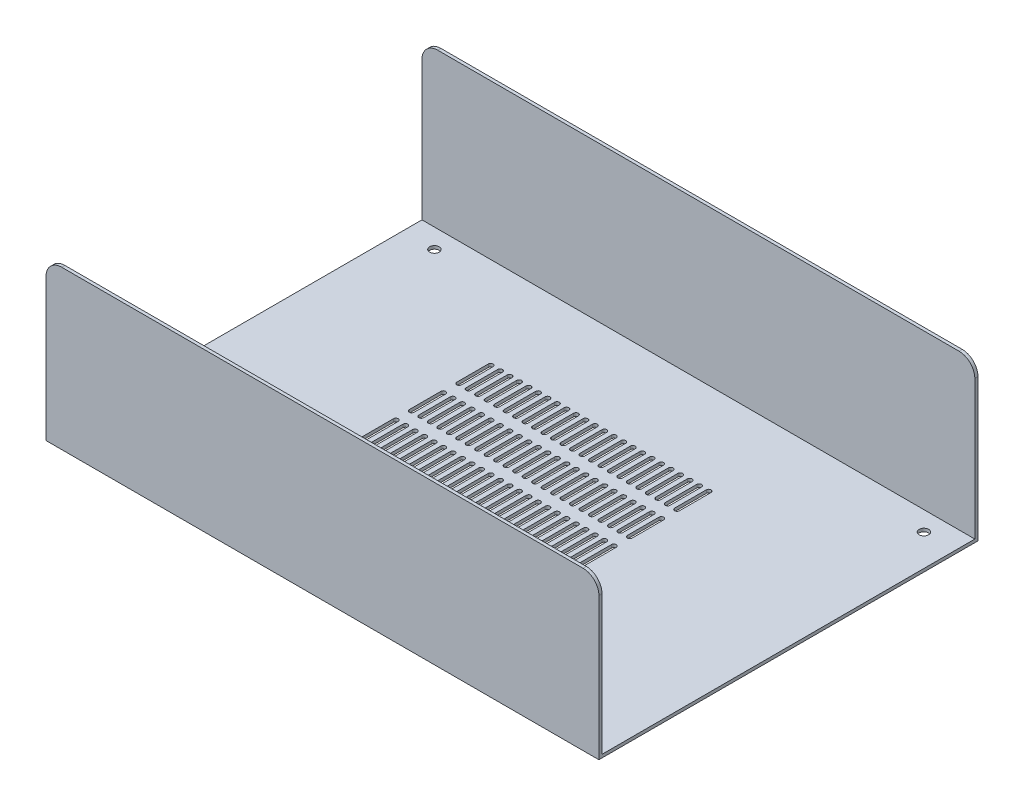
SolidWorks part; units mm, degrees
ref_plane "Front Plane" through (0, 0, 0) normal (0, 0, 1) x (1, 0, 0)
ref_plane "Top Plane" through (0, 0, 0) normal (0, 1, 0) x (1, 0, 0)
ref_plane "Right Plane" through (0, 0, 0) normal (1, 0, 0) x (0, 0, -1)
sketch "Sketch1" plane through (0, 0, 0) normal (0, 1, 0) x (1, 0, 0)
  line L1 (-87.5, 60) -> (87.5, 60)
  line L2 (-87.5, 60) -> (-87.5, -60)
  line L3 (-87.5, -60) -> (87.5, -60)
  line L4 (87.5, 60) -> (87.5, -60)
  point P4 (0, -60)
  point P6 (87.5, 0)
  dimension "D1" = 175
  dimension "D2" = 120
extrude "Extrude1" add sketch "Sketch1" along normal blind 1
sketch "Sketch2" plane through (0, 0, 60) normal (0, 0, 1) x (1, 0, 0)
  line L0 (-87.5, 1) -> (87.5, 1) construction
  line L1 (-82.5, 50) -> (82.5, 50)
  line L2 (-87.5, 45) -> (-87.5, 1)
  line L3 (-87.5, 1) -> (87.5, 1)
  line L4 (87.5, 45) -> (87.5, 1)
  arc A0 (-82.5, 50) -> (-87.5, 45) centre (-82.5, 45) ccw
  arc A1 (82.5, 50) -> (87.5, 45) centre (82.5, 45) cw
  point P9 (-87.5, 50)
  dimension "D2" = 5
  dimension "D1" = 49
extrude "Extrude2" add sketch "Sketch2" against normal blind 1
mirror "Mirror1" about plane through (0, 0, 0) normal (0, 0, 1) of "Extrude2"
sketch "Sketch3" plane through (0, 0, 0) normal (0, -1, 0) x (1, 0, 0)
  circle A0 centre (-77.42, 51.92) radius 1.5
  circle A2 centre (77.52, 51.92) radius 1.5
  circle A3 centre (77.52, 51.92) radius 1.5 construction
  circle A4 centre (77.52, -52.86) radius 1.5
  circle A6 centre (-77.42, -52.86) radius 1.5
  circle A8 centre (-77.42, -52.86) radius 1.5 construction
  circle A9 centre (77.52, -52.86) radius 1.5 construction
extrude "Cut-Extrude1" cut sketch "Sketch3" against normal through all
sketch "Sketch4" plane through (0, 0, 0) normal (0, -1, 0) x (1, 0, 0)
  line L0 (-37.5, 10) -> (-37.5, 0)
  line L1 (-36, 10) -> (-36, 0)
  line L2 (-87.5, -60) -> (-87.5, 60) construction
  line L146 (-87.5, 60) -> (87.5, 60) construction
  line L147 (-34.5, 10) -> (-34.5, 0)
  line L148 (-33, 10) -> (-33, 0)
  line L149 (-31.5, 10) -> (-31.5, 0)
  line L150 (-30, 10) -> (-30, 0)
  line L151 (-28.5, 10) -> (-28.5, 0)
  line L152 (-27, 10) -> (-27, 0)
  line L153 (-25.5, 10) -> (-25.5, 0)
  line L154 (-24, 10) -> (-24, 0)
  line L155 (-22.5, 10) -> (-22.5, 0)
  line L156 (-21, 10) -> (-21, 0)
  line L157 (-19.5, 10) -> (-19.5, 0)
  line L158 (-18, 10) -> (-18, 0)
  line L159 (-16.5, 10) -> (-16.5, 0)
  line L160 (-15, 10) -> (-15, 0)
  line L161 (-13.5, 10) -> (-13.5, 0)
  line L162 (-12, 10) -> (-12, 0)
  line L163 (-10.5, 10) -> (-10.5, 0)
  line L164 (-9, 10) -> (-9, 0)
  line L165 (-7.5, 10) -> (-7.5, 0)
  line L166 (-6, 10) -> (-6, 0)
  line L167 (-4.5, 10) -> (-4.5, 0)
  line L168 (-3, 10) -> (-3, 0)
  line L169 (-1.5, 10) -> (-1.5, 0)
  line L170 (0, 10) -> (0, 0)
  line L171 (1.5, 10) -> (1.5, 0)
  line L172 (3, 10) -> (3, 0)
  line L173 (4.5, 10) -> (4.5, 0)
  line L174 (6, 10) -> (6, 0)
  line L175 (7.5, 10) -> (7.5, 0)
  line L176 (9, 10) -> (9, 0)
  line L177 (10.5, 10) -> (10.5, 0)
  line L178 (12, 10) -> (12, 0)
  line L179 (13.5, 10) -> (13.5, 0)
  line L180 (15, 10) -> (15, 0)
  line L181 (16.5, 10) -> (16.5, 0)
  line L182 (18, 10) -> (18, 0)
  line L183 (19.5, 10) -> (19.5, 0)
  line L184 (21, 10) -> (21, 0)
  line L185 (22.5, 10) -> (22.5, 0)
  line L186 (24, 10) -> (24, 0)
  line L187 (25.5, 10) -> (25.5, 0)
  line L188 (27, 10) -> (27, 0)
  line L189 (28.5, 10) -> (28.5, 0)
  line L190 (30, 10) -> (30, 0)
  line L191 (31.5, 10) -> (31.5, 0)
  line L192 (33, 10) -> (33, 0)
  line L193 (-37.5, -5) -> (-37.5, -15)
  line L194 (-36, -5) -> (-36, -15)
  line L195 (-34.5, -5) -> (-34.5, -15)
  line L196 (-33, -5) -> (-33, -15)
  line L197 (-31.5, -5) -> (-31.5, -15)
  line L198 (-30, -5) -> (-30, -15)
  line L199 (-28.5, -5) -> (-28.5, -15)
  line L200 (-27, -5) -> (-27, -15)
  line L201 (-25.5, -5) -> (-25.5, -15)
  line L202 (-24, -5) -> (-24, -15)
  line L203 (-22.5, -5) -> (-22.5, -15)
  line L204 (-21, -5) -> (-21, -15)
  line L205 (-19.5, -5) -> (-19.5, -15)
  line L206 (-18, -5) -> (-18, -15)
  line L207 (-16.5, -5) -> (-16.5, -15)
  line L208 (-15, -5) -> (-15, -15)
  line L209 (-13.5, -5) -> (-13.5, -15)
  line L210 (-12, -5) -> (-12, -15)
  line L211 (-10.5, -5) -> (-10.5, -15)
  line L212 (-9, -5) -> (-9, -15)
  line L213 (-7.5, -5) -> (-7.5, -15)
  line L214 (-6, -5) -> (-6, -15)
  line L215 (-4.5, -5) -> (-4.5, -15)
  line L216 (-3, -5) -> (-3, -15)
  line L217 (-1.5, -5) -> (-1.5, -15)
  line L218 (0, -5) -> (0, -15)
  line L219 (1.5, -5) -> (1.5, -15)
  line L220 (3, -5) -> (3, -15)
  line L221 (4.5, -5) -> (4.5, -15)
  line L222 (6, -5) -> (6, -15)
  line L223 (7.5, -5) -> (7.5, -15)
  line L224 (9, -5) -> (9, -15)
  line L225 (10.5, -5) -> (10.5, -15)
  line L226 (12, -5) -> (12, -15)
  line L227 (13.5, -5) -> (13.5, -15)
  line L228 (15, -5) -> (15, -15)
  line L229 (16.5, -5) -> (16.5, -15)
  line L230 (18, -5) -> (18, -15)
  line L231 (19.5, -5) -> (19.5, -15)
  line L232 (21, -5) -> (21, -15)
  line L233 (22.5, -5) -> (22.5, -15)
  line L234 (24, -5) -> (24, -15)
  line L235 (25.5, -5) -> (25.5, -15)
  line L236 (27, -5) -> (27, -15)
  line L237 (28.5, -5) -> (28.5, -15)
  line L238 (30, -5) -> (30, -15)
  line L239 (31.5, -5) -> (31.5, -15)
  line L240 (33, -5) -> (33, -15)
  line L241 (-37.5, -20) -> (-37.5, -30)
  line L242 (-36, -20) -> (-36, -30)
  line L243 (-34.5, -20) -> (-34.5, -30)
  line L244 (-33, -20) -> (-33, -30)
  line L245 (-31.5, -20) -> (-31.5, -30)
  line L246 (-30, -20) -> (-30, -30)
  line L247 (-28.5, -20) -> (-28.5, -30)
  line L248 (-27, -20) -> (-27, -30)
  line L249 (-25.5, -20) -> (-25.5, -30)
  line L250 (-24, -20) -> (-24, -30)
  line L251 (-22.5, -20) -> (-22.5, -30)
  line L252 (-21, -20) -> (-21, -30)
  line L253 (-19.5, -20) -> (-19.5, -30)
  line L254 (-18, -20) -> (-18, -30)
  line L255 (-16.5, -20) -> (-16.5, -30)
  line L256 (-15, -20) -> (-15, -30)
  line L257 (-13.5, -20) -> (-13.5, -30)
  line L258 (-12, -20) -> (-12, -30)
  line L259 (-10.5, -20) -> (-10.5, -30)
  line L260 (-9, -20) -> (-9, -30)
  line L261 (-7.5, -20) -> (-7.5, -30)
  line L262 (-6, -20) -> (-6, -30)
  line L263 (-4.5, -20) -> (-4.5, -30)
  line L264 (-3, -20) -> (-3, -30)
  line L265 (-1.5, -20) -> (-1.5, -30)
  line L266 (0, -20) -> (0, -30)
  line L267 (1.5, -20) -> (1.5, -30)
  line L268 (3, -20) -> (3, -30)
  line L269 (4.5, -20) -> (4.5, -30)
  line L270 (6, -20) -> (6, -30)
  line L271 (7.5, -20) -> (7.5, -30)
  line L272 (9, -20) -> (9, -30)
  line L273 (10.5, -20) -> (10.5, -30)
  line L274 (12, -20) -> (12, -30)
  line L275 (13.5, -20) -> (13.5, -30)
  line L276 (15, -20) -> (15, -30)
  line L277 (16.5, -20) -> (16.5, -30)
  line L278 (18, -20) -> (18, -30)
  line L279 (19.5, -20) -> (19.5, -30)
  line L280 (21, -20) -> (21, -30)
  line L281 (22.5, -20) -> (22.5, -30)
  line L282 (24, -20) -> (24, -30)
  line L283 (25.5, -20) -> (25.5, -30)
  line L284 (27, -20) -> (27, -30)
  line L285 (28.5, -20) -> (28.5, -30)
  line L286 (30, -20) -> (30, -30)
  line L287 (31.5, -20) -> (31.5, -30)
  line L288 (33, -20) -> (33, -30)
  arc A0 (-37.5, 10) -> (-36, 10) centre (-36.75, 10) cw
  arc A1 (-36, 0) -> (-37.5, 0) centre (-36.75, 0) cw
  arc A144 (-34.5, 10) -> (-33, 10) centre (-33.75, 10) cw
  arc A145 (-33, 0) -> (-34.5, 0) centre (-33.75, 0) cw
  arc A146 (-31.5, 10) -> (-30, 10) centre (-30.75, 10) cw
  arc A147 (-30, 0) -> (-31.5, 0) centre (-30.75, 0) cw
  arc A148 (-28.5, 10) -> (-27, 10) centre (-27.75, 10) cw
  arc A149 (-27, 0) -> (-28.5, 0) centre (-27.75, 0) cw
  arc A150 (-25.5, 10) -> (-24, 10) centre (-24.75, 10) cw
  arc A151 (-24, 0) -> (-25.5, 0) centre (-24.75, 0) cw
  arc A152 (-22.5, 10) -> (-21, 10) centre (-21.75, 10) cw
  arc A153 (-21, 0) -> (-22.5, 0) centre (-21.75, 0) cw
  arc A154 (-19.5, 10) -> (-18, 10) centre (-18.75, 10) cw
  arc A155 (-18, 0) -> (-19.5, 0) centre (-18.75, 0) cw
  arc A156 (-16.5, 10) -> (-15, 10) centre (-15.75, 10) cw
  arc A157 (-15, 0) -> (-16.5, 0) centre (-15.75, 0) cw
  arc A158 (-13.5, 10) -> (-12, 10) centre (-12.75, 10) cw
  arc A159 (-12, 0) -> (-13.5, 0) centre (-12.75, 0) cw
  arc A160 (-10.5, 10) -> (-9, 10) centre (-9.75, 10) cw
  arc A161 (-9, 0) -> (-10.5, 0) centre (-9.75, 0) cw
  arc A162 (-7.5, 10) -> (-6, 10) centre (-6.75, 10) cw
  arc A163 (-6, 0) -> (-7.5, 0) centre (-6.75, 0) cw
  arc A164 (-4.5, 10) -> (-3, 10) centre (-3.75, 10) cw
  arc A165 (-3, 0) -> (-4.5, 0) centre (-3.75, 0) cw
  arc A166 (-1.5, 10) -> (0, 10) centre (-0.75, 10) cw
  arc A167 (0, 0) -> (-1.5, 0) centre (-0.75, 0) cw
  arc A168 (1.5, 10) -> (3, 10) centre (2.25, 10) cw
  arc A169 (3, 0) -> (1.5, 0) centre (2.25, 0) cw
  arc A170 (4.5, 10) -> (6, 10) centre (5.25, 10) cw
  arc A171 (6, 0) -> (4.5, 0) centre (5.25, 0) cw
  arc A172 (7.5, 10) -> (9, 10) centre (8.25, 10) cw
  arc A173 (9, 0) -> (7.5, 0) centre (8.25, 0) cw
  arc A174 (10.5, 10) -> (12, 10) centre (11.25, 10) cw
  arc A175 (12, 0) -> (10.5, 0) centre (11.25, 0) cw
  arc A176 (13.5, 10) -> (15, 10) centre (14.25, 10) cw
  arc A177 (15, 0) -> (13.5, 0) centre (14.25, 0) cw
  arc A178 (16.5, 10) -> (18, 10) centre (17.25, 10) cw
  arc A179 (18, 0) -> (16.5, 0) centre (17.25, 0) cw
  arc A180 (19.5, 10) -> (21, 10) centre (20.25, 10) cw
  arc A181 (21, 0) -> (19.5, 0) centre (20.25, 0) cw
  arc A182 (22.5, 10) -> (24, 10) centre (23.25, 10) cw
  arc A183 (24, 0) -> (22.5, 0) centre (23.25, 0) cw
  arc A184 (25.5, 10) -> (27, 10) centre (26.25, 10) cw
  arc A185 (27, 0) -> (25.5, 0) centre (26.25, 0) cw
  arc A186 (28.5, 10) -> (30, 10) centre (29.25, 10) cw
  arc A187 (30, 0) -> (28.5, 0) centre (29.25, 0) cw
  arc A188 (31.5, 10) -> (33, 10) centre (32.25, 10) cw
  arc A189 (33, 0) -> (31.5, 0) centre (32.25, 0) cw
  arc A190 (-37.5, -5) -> (-36, -5) centre (-36.75, -5) cw
  arc A191 (-36, -15) -> (-37.5, -15) centre (-36.75, -15) cw
  arc A192 (-34.5, -5) -> (-33, -5) centre (-33.75, -5) cw
  arc A193 (-33, -15) -> (-34.5, -15) centre (-33.75, -15) cw
  arc A194 (-31.5, -5) -> (-30, -5) centre (-30.75, -5) cw
  arc A195 (-30, -15) -> (-31.5, -15) centre (-30.75, -15) cw
  arc A196 (-28.5, -5) -> (-27, -5) centre (-27.75, -5) cw
  arc A197 (-27, -15) -> (-28.5, -15) centre (-27.75, -15) cw
  arc A198 (-25.5, -5) -> (-24, -5) centre (-24.75, -5) cw
  arc A199 (-24, -15) -> (-25.5, -15) centre (-24.75, -15) cw
  arc A200 (-22.5, -5) -> (-21, -5) centre (-21.75, -5) cw
  arc A201 (-21, -15) -> (-22.5, -15) centre (-21.75, -15) cw
  arc A202 (-19.5, -5) -> (-18, -5) centre (-18.75, -5) cw
  arc A203 (-18, -15) -> (-19.5, -15) centre (-18.75, -15) cw
  arc A204 (-16.5, -5) -> (-15, -5) centre (-15.75, -5) cw
  arc A205 (-15, -15) -> (-16.5, -15) centre (-15.75, -15) cw
  arc A206 (-13.5, -5) -> (-12, -5) centre (-12.75, -5) cw
  arc A207 (-12, -15) -> (-13.5, -15) centre (-12.75, -15) cw
  arc A208 (-10.5, -5) -> (-9, -5) centre (-9.75, -5) cw
  arc A209 (-9, -15) -> (-10.5, -15) centre (-9.75, -15) cw
  arc A210 (-7.5, -5) -> (-6, -5) centre (-6.75, -5) cw
  arc A211 (-6, -15) -> (-7.5, -15) centre (-6.75, -15) cw
  arc A212 (-4.5, -5) -> (-3, -5) centre (-3.75, -5) cw
  arc A213 (-3, -15) -> (-4.5, -15) centre (-3.75, -15) cw
  arc A214 (-1.5, -5) -> (0, -5) centre (-0.75, -5) cw
  arc A215 (0, -15) -> (-1.5, -15) centre (-0.75, -15) cw
  arc A216 (1.5, -5) -> (3, -5) centre (2.25, -5) cw
  arc A217 (3, -15) -> (1.5, -15) centre (2.25, -15) cw
  arc A218 (4.5, -5) -> (6, -5) centre (5.25, -5) cw
  arc A219 (6, -15) -> (4.5, -15) centre (5.25, -15) cw
  arc A220 (7.5, -5) -> (9, -5) centre (8.25, -5) cw
  arc A221 (9, -15) -> (7.5, -15) centre (8.25, -15) cw
  arc A222 (10.5, -5) -> (12, -5) centre (11.25, -5) cw
  arc A223 (12, -15) -> (10.5, -15) centre (11.25, -15) cw
  arc A224 (13.5, -5) -> (15, -5) centre (14.25, -5) cw
  arc A225 (15, -15) -> (13.5, -15) centre (14.25, -15) cw
  arc A226 (16.5, -5) -> (18, -5) centre (17.25, -5) cw
  arc A227 (18, -15) -> (16.5, -15) centre (17.25, -15) cw
  arc A228 (19.5, -5) -> (21, -5) centre (20.25, -5) cw
  arc A229 (21, -15) -> (19.5, -15) centre (20.25, -15) cw
  arc A230 (22.5, -5) -> (24, -5) centre (23.25, -5) cw
  arc A231 (24, -15) -> (22.5, -15) centre (23.25, -15) cw
  arc A232 (25.5, -5) -> (27, -5) centre (26.25, -5) cw
  arc A233 (27, -15) -> (25.5, -15) centre (26.25, -15) cw
  arc A234 (28.5, -5) -> (30, -5) centre (29.25, -5) cw
  arc A235 (30, -15) -> (28.5, -15) centre (29.25, -15) cw
  arc A236 (31.5, -5) -> (33, -5) centre (32.25, -5) cw
  arc A237 (33, -15) -> (31.5, -15) centre (32.25, -15) cw
  arc A238 (-37.5, -20) -> (-36, -20) centre (-36.75, -20) cw
  arc A239 (-36, -30) -> (-37.5, -30) centre (-36.75, -30) cw
  arc A240 (-34.5, -20) -> (-33, -20) centre (-33.75, -20) cw
  arc A241 (-33, -30) -> (-34.5, -30) centre (-33.75, -30) cw
  arc A242 (-31.5, -20) -> (-30, -20) centre (-30.75, -20) cw
  arc A243 (-30, -30) -> (-31.5, -30) centre (-30.75, -30) cw
  arc A244 (-28.5, -20) -> (-27, -20) centre (-27.75, -20) cw
  arc A245 (-27, -30) -> (-28.5, -30) centre (-27.75, -30) cw
  arc A246 (-25.5, -20) -> (-24, -20) centre (-24.75, -20) cw
  arc A247 (-24, -30) -> (-25.5, -30) centre (-24.75, -30) cw
  arc A248 (-22.5, -20) -> (-21, -20) centre (-21.75, -20) cw
  arc A249 (-21, -30) -> (-22.5, -30) centre (-21.75, -30) cw
  arc A250 (-19.5, -20) -> (-18, -20) centre (-18.75, -20) cw
  arc A251 (-18, -30) -> (-19.5, -30) centre (-18.75, -30) cw
  arc A252 (-16.5, -20) -> (-15, -20) centre (-15.75, -20) cw
  arc A253 (-15, -30) -> (-16.5, -30) centre (-15.75, -30) cw
  arc A254 (-13.5, -20) -> (-12, -20) centre (-12.75, -20) cw
  arc A255 (-12, -30) -> (-13.5, -30) centre (-12.75, -30) cw
  arc A256 (-10.5, -20) -> (-9, -20) centre (-9.75, -20) cw
  arc A257 (-9, -30) -> (-10.5, -30) centre (-9.75, -30) cw
  arc A258 (-7.5, -20) -> (-6, -20) centre (-6.75, -20) cw
  arc A259 (-6, -30) -> (-7.5, -30) centre (-6.75, -30) cw
  arc A260 (-4.5, -20) -> (-3, -20) centre (-3.75, -20) cw
  arc A261 (-3, -30) -> (-4.5, -30) centre (-3.75, -30) cw
  arc A262 (-1.5, -20) -> (0, -20) centre (-0.75, -20) cw
  arc A263 (0, -30) -> (-1.5, -30) centre (-0.75, -30) cw
  arc A264 (1.5, -20) -> (3, -20) centre (2.25, -20) cw
  arc A265 (3, -30) -> (1.5, -30) centre (2.25, -30) cw
  arc A266 (4.5, -20) -> (6, -20) centre (5.25, -20) cw
  arc A267 (6, -30) -> (4.5, -30) centre (5.25, -30) cw
  arc A268 (7.5, -20) -> (9, -20) centre (8.25, -20) cw
  arc A269 (9, -30) -> (7.5, -30) centre (8.25, -30) cw
  arc A270 (10.5, -20) -> (12, -20) centre (11.25, -20) cw
  arc A271 (12, -30) -> (10.5, -30) centre (11.25, -30) cw
  arc A272 (13.5, -20) -> (15, -20) centre (14.25, -20) cw
  arc A273 (15, -30) -> (13.5, -30) centre (14.25, -30) cw
  arc A274 (16.5, -20) -> (18, -20) centre (17.25, -20) cw
  arc A275 (18, -30) -> (16.5, -30) centre (17.25, -30) cw
  arc A276 (19.5, -20) -> (21, -20) centre (20.25, -20) cw
  arc A277 (21, -30) -> (19.5, -30) centre (20.25, -30) cw
  arc A278 (22.5, -20) -> (24, -20) centre (23.25, -20) cw
  arc A279 (24, -30) -> (22.5, -30) centre (23.25, -30) cw
  arc A280 (25.5, -20) -> (27, -20) centre (26.25, -20) cw
  arc A281 (27, -30) -> (25.5, -30) centre (26.25, -30) cw
  arc A282 (28.5, -20) -> (30, -20) centre (29.25, -20) cw
  arc A283 (30, -30) -> (28.5, -30) centre (29.25, -30) cw
  arc A284 (31.5, -20) -> (33, -20) centre (32.25, -20) cw
  arc A285 (33, -30) -> (31.5, -30) centre (32.25, -30) cw
  dimension "D4" = 50
  dimension "D1" = 10
  dimension "D2" = 1.5
  dimension "D3" = 50
extrude "Extrude3" cut sketch "Sketch4" against normal up to next (1 mm away)
